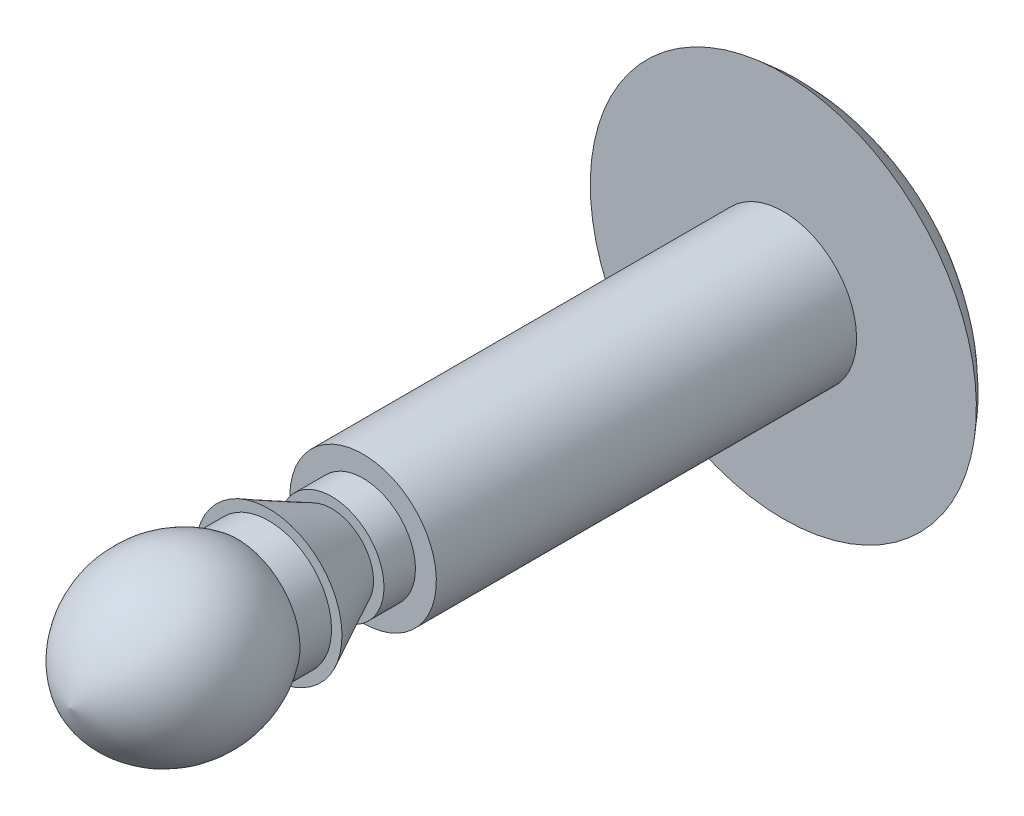
SolidWorks part; units mm, degrees
ref_plane "Front" through (0, 0, 0) normal (0, 0, 1) x (1, 0, 0)
ref_plane "Top" through (0, 0, 0) normal (0, 1, 0) x (1, 0, 0)
ref_plane "Right" through (0, 0, 0) normal (1, 0, 0) x (0, 0, -1)
sketch "Layout" plane through (0, 0, 0) normal (1, 0, 0) x (0, 0, -1)
  line L0 (-9.7536, 0) -> (-6.5024, 0) construction
  line L1 (-6.5024, 0) -> (-3.2512, 0) construction
  line L2 (-9.7536, 0) -> (-13.0048, 0) construction
  line L3 (0, 0) -> (0, 4.5974) construction
  line L4 (-9.7536, 0) -> (-9.7536, 1.9939) construction
  line L5 (-3.2512, 0) -> (0, 0) construction
  line L6 (-14.9987, 0) -> (-14.9987, 1.9939) construction
  line L7 (0, 0) -> (18.3896, 0) construction
  line L8 (1.397, 0) -> (1.397, 4.5974) construction
  line L9 (-14.9987, 0) -> (-16.9926, 0) construction
  circle A0 centre (-14.9987, 0) radius 1.9939 construction
  dimension "D5" = 16.9926
  dimension "D6" = 16.9926
sketch "Sketch2" plane through (0, 0, 0) normal (1, 0, 0) x (0, 0, -1)
  line L0 (1.397, 0) -> (1.397, 4.5974) construction
  line L1 (-10.0076, 1.7447) -> (-10.0076, 1.2462)
  line L2 (0, 1.7447) -> (-10.0076, 1.7447)
  line L3 (0, 0) -> (0, 4.5974) construction
  line L4 (0, 1.7447) -> (0, 4.5974)
  line L5 (1.397, 0.9969) -> (17.8911, 0.9969)
  line L6 (17.8911, 0.9969) -> (18.3896, 0)
  line L7 (-9.7536, 0.9969) -> (1.397, 0.9969) construction
  line L8 (17.8911, 0.9969) -> (17.8911, 0.4985) construction
  line L9 (17.8911, 0.4985) -> (17.8911, 0) construction
  line L10 (0, 0) -> (18.3896, 0) construction
  line L11 (17.8911, 0) -> (18.3896, 0) construction
  line L12 (-9.7536, 0) -> (-9.7536, 1.9939) construction
  line L13 (-14.9987, 1.9939) -> (-10.0076, 1.9939) construction
  line L14 (-13.0048, 1.4954) -> (-12.2555, 1.4954) construction
  line L16 (-13.0048, 1.4954) -> (-12.2555, 1.4954)
  line L17 (-9.6667, 0) -> (18.3896, 0)
  line L18 (-12.2555, 1.4954) -> (-12.2555, 1.7447)
  line L19 (-12.2555, 1.7447) -> (-10.7569, 0.9969)
  line L20 (-12.2555, 1.4954) -> (-11.5062, 1.4954) construction
  line L21 (-10.7569, 0.9969) -> (-10.7569, 1.2462)
  line L22 (-10.7569, 1.2462) -> (-10.0076, 1.2462)
  line L23 (-9.6667, 0) -> (-16.9926, 0)
  line L24 (-10.0076, 1.4954) -> (-10.0076, 1.2462) construction
  line L25 (-10.0076, 1.2462) -> (-10.0076, 0.9969) construction
  line L26 (-11.5062, 1.4954) -> (-10.7569, 1.4954) construction
  line L27 (-10.7569, 1.4954) -> (-10.0076, 1.4954) construction
  line L28 (-10.0076, 1.9939) -> (-10.0076, 1.7447) construction
  line L29 (1.397, 1.7589) -> (0.635, 1.7589) construction
  line L30 (0.635, 1.7589) -> (0.635, 0.9969) construction
  line L31 (1.016, 1.7589) -> (1.016, 0.9969) construction
  line L32 (1.397, 0.9969) -> (1.016, 0.9969)
  line L33 (1.016, 0.9969) -> (1.016, 1.099)
  arc A0 (0, 4.5974) -> (1.397, 1.7589) centre (-2.1851, 1.7589) cw
  arc A2 (-13.0048, 1.4954) -> (-16.9926, 0) centre (-14.5148, -0.5426) ccw
  arc A3 (1.397, 1.7589) -> (1.016, 1.099) centre (0.635, 1.7589) cw
  arc A4 (1.016, 1.099) -> (0.635, 0.9969) centre (0.635, 1.7589) cw construction
  dimension "D1" = 0.762
  dimension "Mat thick max" = 10.0076
revolve "Revolve1" add sketch "Sketch2" angle 360 about L17
ref_plane "Plane1" through (0, 0, -1.397) normal (0, 0, 1) x (1, 0, 0)
sketch "Sketch3" plane through (0, 0, -1.397) normal (0, 0, 1) x (1, 0, 0)
  circle A0 centre (0, 0) radius 10.4524
extrude "Cut-Extrude1" cut sketch "Sketch3" against normal through all
equation "\"D6@Layout\"=\"D5@Layout\""
